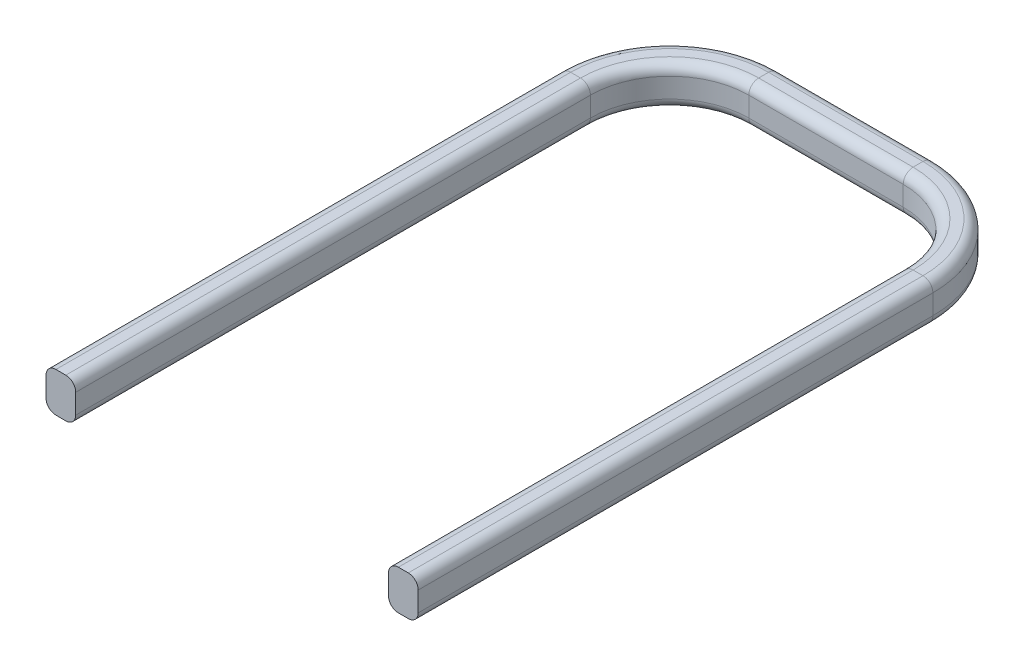
SolidWorks part; units mm, degrees
ref_plane "Front Plane" through (0, 0, 0) normal (0, 0, 1) x (1, 0, 0)
ref_plane "Top Plane" through (0, 0, 0) normal (0, 1, 0) x (1, 0, 0)
ref_plane "Right Plane" through (0, 0, 0) normal (1, 0, 0) x (0, 0, -1)
sketch "Sketch1" plane through (0, 0, 0) normal (0, 1, 0) x (1, 0, 0)
  line L0 (-3.95, 0) -> (-3.95, 13)
  line L1 (-1.95, 15) -> (1.95, 15)
  line L2 (3.95, 13) -> (3.95, 0)
  arc A0 (1.95, 15) -> (3.95, 13) centre (1.95, 13) cw
  arc A1 (-3.95, 13) -> (-1.95, 15) centre (-1.95, 13) cw
  point P6 (0, 15)
  point P11 (-3.95, 15)
  dimension "D3" = 2
  dimension "D1" = 3.95
  dimension "D2" = 15
sketch "Sketch2" plane through (0, 0, 0) normal (0, 0, 1) x (1, 0, 0)
  line L1 (-3.95, 0) -> (-4.7, 0)
  line L2 (-3.95, 0) -> (-3.95, 1)
  line L3 (-3.95, 1) -> (-4.7, 1)
  line L4 (-4.7, 0) -> (-4.7, 1)
  dimension "D1" = 1
  dimension "D2" = 0.75
sweep "Sweep1" add profiles "Sketch2" path "Sketch1"
fillet "Fillet1" radius 0.25 20 edges at (4.7, 0, -6.5) (3.8945, 0, -14.9445) (0, 0, -15.75) (-3.8945, 0, -14.9445) (3.95, 0, -6.5) (3.3642, 0, -14.4142) (0, 0, -15) (-3.3642, 0, -14.4142) (3.95, 1, -6.5) (3.3642, 1, -14.4142) (0, 1, -15) (-3.3642, 1, -14.4142) (4.7, 1, -6.5) (3.8945, 1, -14.9445) (0, 1, -15.75) (-3.8945, 1, -14.9445) (-4.7, 0, -6.5) (-3.95, 0, -6.5) (-3.95, 1, -6.5) (-4.7, 1, -6.5)
scale "Scale1" scale about origin uniform scaling yes scale factor 0.445
